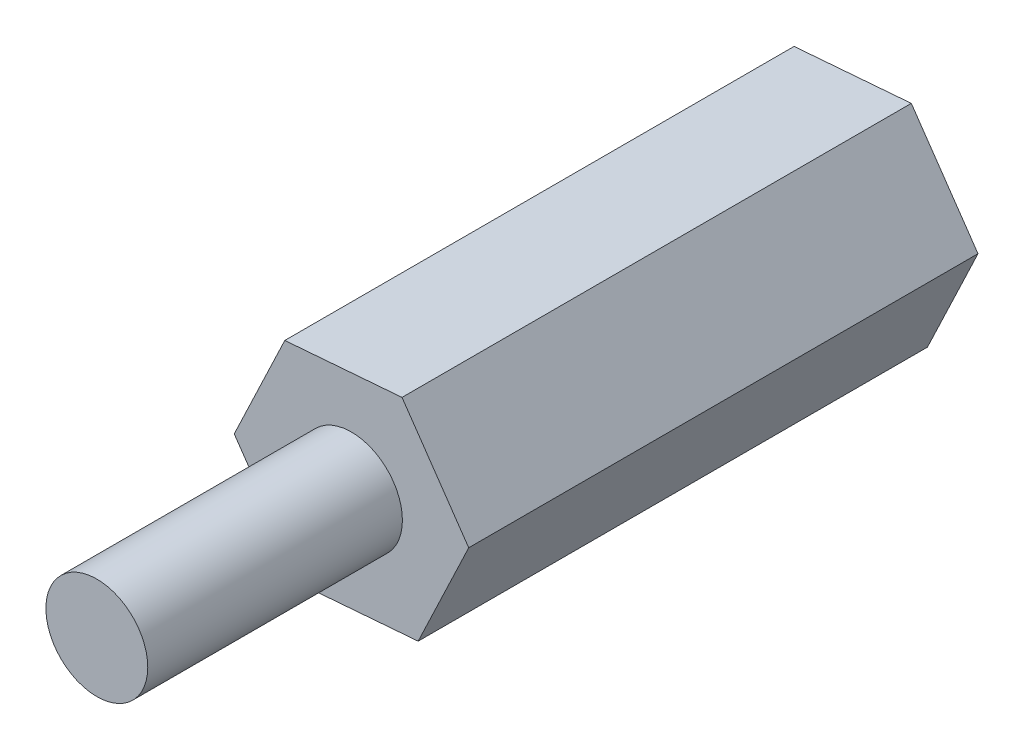
SolidWorks part; units mm, degrees
ref_plane "Plan de face" through (0, 0, 0) normal (0, 0, 1) x (1, 0, 0)
ref_plane "Plan de dessus" through (0, 0, 0) normal (0, 1, 0) x (1, 0, 0)
ref_plane "Plan de droite" through (0, 0, 0) normal (1, 0, 0) x (0, 0, -1)
sketch "Esquisse1" plane through (0, 0, 0) normal (0, 0, 1) x (1, 0, 0)
  line L1 (2.3021, 0.1829) -> (0.9927, 2.0852)
  line L2 (0.9927, 2.0852) -> (-1.3095, 1.9023)
  line L3 (-1.3095, 1.9023) -> (-2.3021, -0.1829)
  line L4 (-2.3021, -0.1829) -> (-0.9927, -2.0852)
  line L5 (-0.9927, -2.0852) -> (1.3095, -1.9023)
  line L6 (1.3095, -1.9023) -> (2.3021, 0.1829)
  circle A0 centre (0, 0) radius 2 construction
  dimension "D1" = 4
extrude "Boss.-Extru.1" add sketch "Esquisse1" along normal blind 10
sketch "Esquisse2" plane through (0, 0, 10) normal (0, 0, 1) x (1, 0, 0)
  circle A0 centre (0, 0) radius 1
  dimension "D1" = 2
extrude "Boss.-Extru.2" add sketch "Esquisse2" along normal blind 5
sketch "Esquisse3" plane through (0, 0, 0) normal (0, 0, -1) x (-1, 0, 0)
  circle A0 centre (0, 0) radius 1
  dimension "D1" = 2
extrude "Enlèv. mat.-Extru.1" cut sketch "Esquisse3" against normal blind 5
